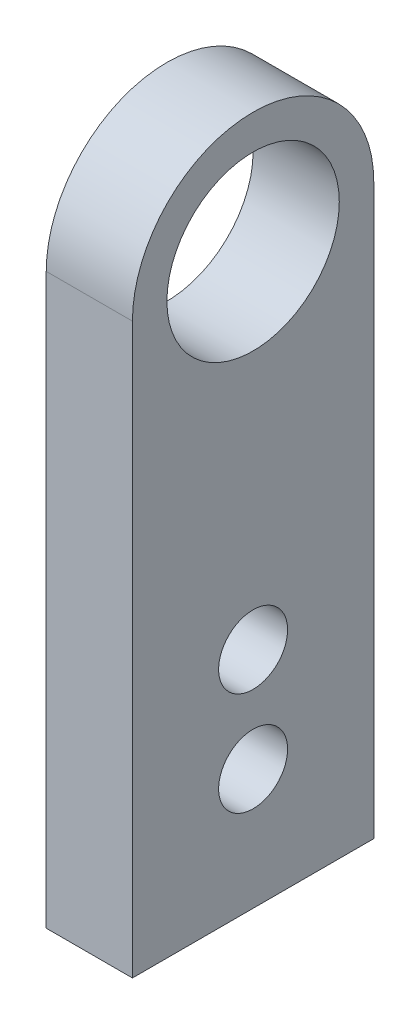
SolidWorks part; units mm, degrees
ref_plane "前视基准面" through (0, 0, 0) normal (0, 0, 1) x (1, 0, 0)
ref_plane "上视基准面" through (0, 0, 0) normal (0, 1, 0) x (1, 0, 0)
ref_plane "右视基准面" through (0, 0, 0) normal (1, 0, 0) x (0, 0, -1)
sketch "草图1" plane through (0, 0, 0) normal (1, 0, 0) x (0, 0, -1)
  line L2 (-7, 33) -> (-7, 0)
  line L3 (-7, 0) -> (7, 0)
  line L4 (7, 33) -> (7, 0)
  circle A0 centre (0, 33) radius 5
  arc A1 (7, 33) -> (-7, 33) centre (0, 33) ccw
  circle A2 centre (0, 13) radius 2
  circle A3 centre (0, 7) radius 2
  point P4 (0, 0)
  dimension "D3" = 33
  dimension "D2" = 7
  dimension "D1" = 14
  dimension "D4" = 6
extrude "凸台-拉伸1" add sketch "草图1" along normal blind 5
